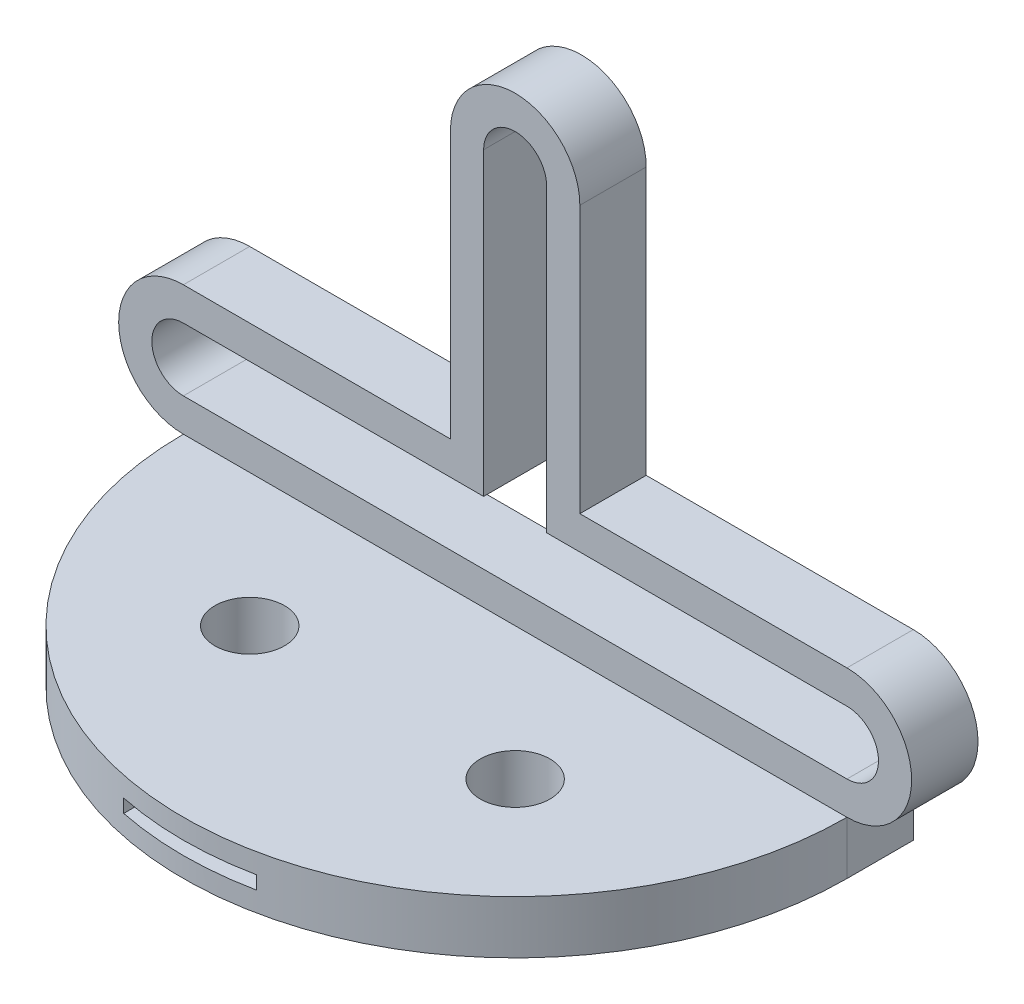
SolidWorks part; units mm, degrees
ref_plane "Front Plane" through (0, 0, 0) normal (0, 0, 1) x (1, 0, 0)
ref_plane "Top Plane" through (0, 0, 0) normal (0, 1, 0) x (1, 0, 0)
ref_plane "Right Plane" through (0, 0, 0) normal (1, 0, 0) x (0, 0, -1)
sketch "Sketch1" plane through (0, 0, 0) normal (0, 0, 1) x (1, 0, 0)
  line L0 (-4.75, 50) -> (-4.75, 4.75)
  line L1 (-4.75, 4.75) -> (-50, 4.75)
  line L2 (4.75, 50) -> (4.75, 4.75)
  line L3 (4.75, 4.75) -> (50, 4.75)
  line L4 (-50, -4.75) -> (50, -4.75)
  line L5 (-9.75, 50) -> (-9.75, 9.75)
  line L6 (-9.75, 9.75) -> (-50, 9.75)
  line L7 (-50, -9.75) -> (50, -9.75)
  line L8 (9.75, 9.75) -> (50, 9.75)
  line L9 (9.75, 50) -> (9.75, 9.75)
  line L10 (-50, -9.75) -> (-50, -17.75)
  line L11 (-50, -17.75) -> (50, -17.75)
  line L12 (50, -17.75) -> (50, -9.75)
  arc A0 (-4.75, 50) -> (4.75, 50) centre (0, 50) cw
  arc A1 (-50, 4.75) -> (-50, -4.75) centre (-50, 0) ccw
  arc A2 (50, 4.75) -> (50, -4.75) centre (50, 0) cw
  arc A3 (-50, 9.75) -> (-50, -9.75) centre (-50, 0) ccw
  arc A4 (50, 9.75) -> (50, -9.75) centre (50, 0) cw
  arc A5 (-9.75, 50) -> (9.75, 50) centre (0, 50) cw
  dimension "D1" = 4.75
  dimension "D2" = 45.25
  dimension "D4" = 8
  dimension "D3" = 5
extrude "Boss-Extrude1" add sketch "Sketch1" against normal blind 10 contours A5 L5 L6 A3 L7 A4 L8 L9 L3 A2 L4 A1 L1 L0 A0 L2 | L11 L12 L7 L10
sketch "Sketch2" plane through (0, -17.75, 0) normal (0, -1, 0) x (1, 0, 0)
  line L0 (-50, 0) -> (50, 0)
  arc A0 (-50, 0) -> (50, 0) centre (0, 0) cw
extrude "Boss-Extrude2" add sketch "Sketch2" against normal blind 8
sketch "Sketch3" plane through (0, -9.75, 0) normal (0, 1, 0) x (1, 0, 0)
  circle A0 centre (20, -20) radius 5.25
  circle A1 centre (-20, -20) radius 5.25
  dimension "D2" = 10.5
  dimension "D1" = 20
  dimension "D3" = 20
  dimension "D4" = 20
extrude "Cut-Extrude1" cut sketch "Sketch3" against normal through all
sketch "Sketch4" plane through (0, 0, -10) normal (0, 0, -1) x (-1, 0, 0)
  line L0 (50, -17.75) -> (-50, -17.75) construction
  line L1 (-10, -12.75) -> (10, -12.75)
  line L2 (-10, -12.75) -> (-10, -14.75)
  line L3 (-10, -14.75) -> (10, -14.75)
  line L4 (10, -12.75) -> (10, -14.75)
  line L5 (-10, -12.75) -> (10, -14.75) construction
  line L6 (-10, -14.75) -> (10, -12.75) construction
  point P0 (0, -13.75)
  dimension "D1" = 3
  dimension "D2" = 2
  dimension "D3" = 20
extrude "Cut-Extrude2" cut sketch "Sketch4" against normal through all
sketch "Sketch5" plane through (0, -17.75, 0) normal (0, -1, 0) x (1, 0, 0)
  circle A0 centre (0, 20) radius 10
  dimension "D1" = 20
  dimension "D2" = 20
extrude "Cut-Extrude3" cut sketch "Sketch5" against normal up to surface (3 mm away) up to face at (0, -14.75, 19.7474)
